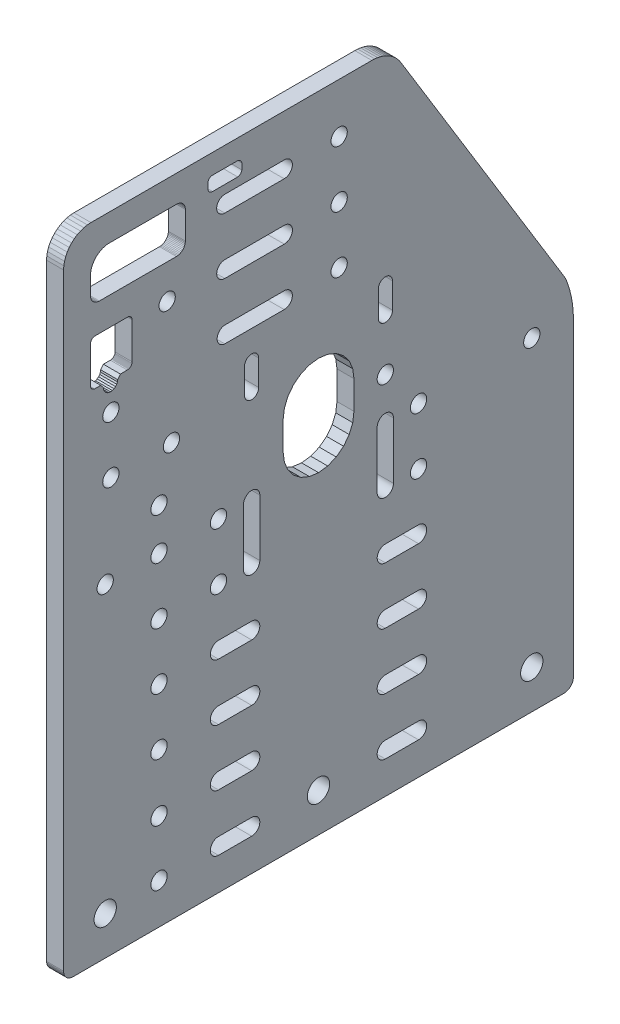
SolidWorks part; units mm, degrees
ref_plane "Front Plane" through (0, 0, 0) normal (0, 0, 1) x (1, 0, 0)
ref_plane "Top Plane" through (0, 0, 0) normal (0, 1, 0) x (1, 0, 0)
ref_plane "Right Plane" through (0, 0, 0) normal (1, 0, 0) x (0, 0, -1)
ref_plane "Plane1" through (0, 0, 0) normal (-1, 0, 0) x (0, -1, 0)
sketch "Sketch1" plane through (0, 0, 0) normal (-1, 0, 0) x (0, -1, 0)
  line L0 (-590.2121, -1614.2437) -> (-495.2304, -1672.3356)
  line L1 (-495.2304, -1672.3356) -> (-492.9855, -1673.1988)
  line L2 (-492.9855, -1673.1988) -> (-490.6881, -1673.9103)
  line L3 (-490.6881, -1673.9103) -> (-488.3483, -1674.4671)
  line L4 (-488.3483, -1674.4671) -> (-485.9766, -1674.8665)
  line L5 (-485.9766, -1674.8665) -> (-483.5835, -1675.1069)
  line L6 (-483.5835, -1675.1069) -> (-481.1798, -1675.1871)
  line L7 (-481.1798, -1675.1871) -> (-371.8266, -1675.1871)
  line L8 (-371.8266, -1675.1871) -> (-371.3877, -1675.1584)
  line L9 (-371.3877, -1675.1584) -> (-370.9562, -1675.0725)
  line L10 (-370.9562, -1675.0725) -> (-370.5397, -1674.9312)
  line L11 (-370.5397, -1674.9312) -> (-370.1452, -1674.7366)
  line L12 (-370.1452, -1674.7366) -> (-369.7795, -1674.4922)
  line L13 (-369.7795, -1674.4922) -> (-369.4487, -1674.2022)
  line L14 (-369.4487, -1674.2022) -> (-369.1587, -1673.8715)
  line L15 (-369.1587, -1673.8715) -> (-368.9143, -1673.5057)
  line L16 (-368.9143, -1673.5057) -> (-368.7198, -1673.1112)
  line L17 (-368.7198, -1673.1112) -> (-368.5784, -1672.6947)
  line L18 (-368.5784, -1672.6947) -> (-368.4926, -1672.2633)
  line L19 (-368.4926, -1672.2633) -> (-368.4638, -1671.8243)
  line L20 (-368.4638, -1671.8243) -> (-368.4638, -1498.5099)
  line L21 (-368.4638, -1498.5099) -> (-368.4926, -1498.071)
  line L22 (-368.4926, -1498.071) -> (-368.5784, -1497.6396)
  line L23 (-368.5784, -1497.6396) -> (-368.7198, -1497.223)
  line L24 (-368.7198, -1497.223) -> (-368.9143, -1496.8285)
  line L25 (-368.9143, -1496.8285) -> (-369.1587, -1496.4628)
  line L26 (-369.1587, -1496.4628) -> (-369.4487, -1496.1321)
  line L27 (-369.4487, -1496.1321) -> (-369.7795, -1495.842)
  line L28 (-369.7795, -1495.842) -> (-370.1452, -1495.5977)
  line L29 (-370.1452, -1495.5977) -> (-370.5397, -1495.4031)
  line L30 (-370.5397, -1495.4031) -> (-370.9562, -1495.2617)
  line L31 (-370.9562, -1495.2617) -> (-371.3877, -1495.1759)
  line L32 (-371.3877, -1495.1759) -> (-371.8266, -1495.1471)
  line L33 (-371.8266, -1495.1471) -> (-586.2881, -1495.1456)
  line L34 (-586.2881, -1495.1456) -> (-587.5497, -1495.2283)
  line L35 (-587.5497, -1495.2283) -> (-588.7897, -1495.475)
  line L36 (-588.7897, -1495.475) -> (-589.987, -1495.8813)
  line L37 (-589.987, -1495.8813) -> (-591.1209, -1496.4405)
  line L38 (-591.1209, -1496.4405) -> (-592.1721, -1497.1429)
  line L39 (-592.1721, -1497.1429) -> (-593.1227, -1497.9766)
  line L40 (-593.1227, -1497.9766) -> (-593.9563, -1498.9271)
  line L41 (-593.9563, -1498.9271) -> (-594.6588, -1499.9784)
  line L42 (-594.6588, -1499.9784) -> (-595.218, -1501.1123)
  line L43 (-595.218, -1501.1123) -> (-595.6244, -1502.3095)
  line L44 (-595.6244, -1502.3095) -> (-595.871, -1503.5495)
  line L45 (-595.871, -1503.5495) -> (-595.9537, -1504.8111)
  line L46 (-595.9537, -1504.8111) -> (-595.9537, -1603.9943)
  line L47 (-595.9537, -1603.9943) -> (-595.9102, -1605.016)
  line L48 (-595.9102, -1605.016) -> (-595.78, -1606.0302)
  line L49 (-595.78, -1606.0302) -> (-595.5641, -1607.0297)
  line L50 (-595.5641, -1607.0297) -> (-595.264, -1608.0073)
  line L51 (-595.264, -1608.0073) -> (-594.8819, -1608.9558)
  line L52 (-594.8819, -1608.9558) -> (-594.4205, -1609.8683)
  line L53 (-594.4205, -1609.8683) -> (-593.8833, -1610.7384)
  line L54 (-593.8833, -1610.7384) -> (-593.274, -1611.5596)
  line L55 (-593.274, -1611.5596) -> (-592.5971, -1612.3261)
  line L56 (-592.5971, -1612.3261) -> (-591.8575, -1613.0323)
  line L57 (-591.8575, -1613.0323) -> (-591.0606, -1613.673)
  line L58 (-591.0606, -1613.673) -> (-590.2121, -1614.2437)
  line L59 (-575.2278, -1552.0779) -> (-575.2278, -1573.0506)
  line L60 (-580.9777, -1573.098) -> (-580.9777, -1552.0841)
  line L61 (-535.2278, -1552.0792) -> (-535.2278, -1573.052)
  line L62 (-540.9777, -1573.0993) -> (-540.9777, -1552.0854)
  line L63 (-555.2276, -1552.095) -> (-555.2276, -1573.0814)
  line L64 (-560.9776, -1573.1131) -> (-560.9776, -1552.0992)
  line L65 (-524.9137, -1559.0552) -> (-515.9137, -1559.0552)
  line L66 (-515.9137, -1564.0552) -> (-524.9137, -1564.0552)
  line L67 (-524.9137, -1606.2991) -> (-515.9137, -1606.2991)
  line L68 (-515.9137, -1611.2991) -> (-524.9137, -1611.2991)
  line L69 (-477.6698, -1606.2991) -> (-468.6699, -1606.2991)
  line L70 (-468.6699, -1611.2991) -> (-477.6698, -1611.2991)
  line L71 (-477.6698, -1559.0528) -> (-468.6699, -1559.0552)
  line L72 (-468.6712, -1564.0552) -> (-477.6698, -1564.0528)
  line L73 (-586.0336, -1536.5791) -> (-586.215, -1536.2112)
  line L74 (-586.215, -1536.2112) -> (-586.3468, -1535.8228)
  line L75 (-586.3468, -1535.8228) -> (-586.4269, -1535.4204)
  line L76 (-586.4269, -1535.4204) -> (-586.4537, -1535.0111)
  line L77 (-586.4537, -1535.0111) -> (-586.4537, -1511.2962)
  line L78 (-586.4537, -1511.2962) -> (-586.3968, -1510.4284)
  line L79 (-586.3968, -1510.4284) -> (-586.2271, -1509.5753)
  line L80 (-586.2271, -1509.5753) -> (-585.9476, -1508.7517)
  line L81 (-585.9476, -1508.7517) -> (-585.5629, -1507.9717)
  line L82 (-585.5629, -1507.9717) -> (-585.0797, -1507.2485)
  line L83 (-585.0797, -1507.2485) -> (-584.5062, -1506.5946)
  line L84 (-584.5062, -1506.5946) -> (-583.8523, -1506.0211)
  line L85 (-583.8523, -1506.0211) -> (-583.1291, -1505.5379)
  line L86 (-583.1291, -1505.5379) -> (-582.3491, -1505.1533)
  line L87 (-582.3491, -1505.1533) -> (-581.5255, -1504.8737)
  line L88 (-581.5255, -1504.8737) -> (-580.6725, -1504.704)
  line L89 (-580.6725, -1504.704) -> (-579.8046, -1504.6471)
  line L90 (-579.8046, -1504.6471) -> (-573.6169, -1504.6471)
  line L91 (-573.6169, -1504.6471) -> (-573.2076, -1504.6739)
  line L92 (-573.2076, -1504.6739) -> (-572.8052, -1504.754)
  line L93 (-572.8052, -1504.754) -> (-572.4168, -1504.8858)
  line L94 (-572.4168, -1504.8858) -> (-572.0489, -1505.0673)
  line L95 (-572.0489, -1505.0673) -> (-571.7078, -1505.2952)
  line L96 (-571.7078, -1505.2952) -> (-571.3994, -1505.5656)
  line L97 (-571.3994, -1505.5656) -> (-571.1289, -1505.8741)
  line L98 (-571.1289, -1505.8741) -> (-570.901, -1506.2151)
  line L99 (-570.901, -1506.2151) -> (-570.7196, -1506.583)
  line L100 (-570.7196, -1506.583) -> (-570.5877, -1506.9715)
  line L101 (-570.5877, -1506.9715) -> (-570.5077, -1507.3738)
  line L102 (-570.5077, -1507.3738) -> (-570.4809, -1507.7831)
  line L103 (-570.4809, -1507.7831) -> (-570.4809, -1535.0111)
  line L104 (-570.4809, -1535.0111) -> (-570.5077, -1535.4204)
  line L105 (-570.5077, -1535.4204) -> (-570.5877, -1535.8228)
  line L106 (-570.5877, -1535.8228) -> (-570.7196, -1536.2112)
  line L107 (-570.7196, -1536.2112) -> (-570.901, -1536.5791)
  line L108 (-570.901, -1536.5791) -> (-571.1289, -1536.9202)
  line L109 (-571.1289, -1536.9202) -> (-571.3994, -1537.2286)
  line L110 (-571.3994, -1537.2286) -> (-571.7078, -1537.4991)
  line L111 (-571.7078, -1537.4991) -> (-572.0489, -1537.727)
  line L112 (-572.0489, -1537.727) -> (-572.4168, -1537.9084)
  line L113 (-572.4168, -1537.9084) -> (-572.8052, -1538.0403)
  line L114 (-572.8052, -1538.0403) -> (-573.2076, -1538.1203)
  line L115 (-573.2076, -1538.1203) -> (-573.6169, -1538.1471)
  line L116 (-573.6169, -1538.1471) -> (-583.3177, -1538.1471)
  line L117 (-583.3177, -1538.1471) -> (-583.727, -1538.1203)
  line L118 (-583.727, -1538.1203) -> (-584.1293, -1538.0403)
  line L119 (-584.1293, -1538.0403) -> (-584.5178, -1537.9084)
  line L120 (-584.5178, -1537.9084) -> (-584.8857, -1537.727)
  line L121 (-584.8857, -1537.727) -> (-585.2268, -1537.4991)
  line L122 (-585.2268, -1537.4991) -> (-585.5352, -1537.2286)
  line L123 (-585.5352, -1537.2286) -> (-585.8057, -1536.9202)
  line L124 (-585.8057, -1536.9202) -> (-586.0336, -1536.5791)
  line L125 (-560.5397, -1505.8783) -> (-560.4696, -1505.6715)
  line L126 (-560.4696, -1505.6715) -> (-560.373, -1505.4757)
  line L127 (-560.373, -1505.4757) -> (-560.2517, -1505.2942)
  line L128 (-560.2517, -1505.2942) -> (-560.1078, -1505.1301)
  line L129 (-560.1078, -1505.1301) -> (-559.9436, -1504.9862)
  line L130 (-559.9436, -1504.9862) -> (-559.7621, -1504.8649)
  line L131 (-559.7621, -1504.8649) -> (-559.5663, -1504.7683)
  line L132 (-559.5663, -1504.7683) -> (-559.3596, -1504.6981)
  line L133 (-559.3596, -1504.6981) -> (-559.1312, -1504.6471)
  line L134 (-559.1312, -1504.6471) -> (-558.9276, -1504.6413)
  line L135 (-558.9276, -1504.6413) -> (-548.4809, -1504.6452)
  line L136 (-548.4809, -1504.6452) -> (-545.8818, -1504.6452)
  line L137 (-545.8818, -1504.6452) -> (-545.6677, -1504.6877)
  line L138 (-545.6677, -1504.6877) -> (-545.461, -1504.7579)
  line L139 (-545.461, -1504.7579) -> (-545.2652, -1504.8545)
  line L140 (-545.2652, -1504.8545) -> (-545.0837, -1504.9758)
  line L141 (-545.0837, -1504.9758) -> (-544.9196, -1505.1197)
  line L142 (-544.9196, -1505.1197) -> (-544.7756, -1505.2838)
  line L143 (-544.7756, -1505.2838) -> (-544.6543, -1505.4654)
  line L144 (-544.6543, -1505.4654) -> (-544.5578, -1505.6612)
  line L145 (-544.5578, -1505.6612) -> (-544.4876, -1505.8679)
  line L146 (-544.4876, -1505.8679) -> (-544.445, -1506.082)
  line L147 (-544.445, -1506.082) -> (-544.4414, -1508.2677)
  line L148 (-544.4414, -1508.2677) -> (-543.221, -1509.2377)
  line L149 (-543.221, -1509.2377) -> (-542.574, -1509.3226)
  line L150 (-542.574, -1509.3226) -> (-541.9709, -1509.5721)
  line L151 (-541.9709, -1509.5721) -> (-541.453, -1509.9692)
  line L152 (-541.453, -1509.9692) -> (-541.0555, -1510.4868)
  line L153 (-541.0555, -1510.4868) -> (-540.8055, -1511.0897)
  line L154 (-540.8055, -1511.0897) -> (-540.72, -1511.7367)
  line L155 (-540.72, -1511.7367) -> (-540.805, -1512.3838)
  line L156 (-540.805, -1512.3838) -> (-541.0545, -1512.9868)
  line L157 (-541.0545, -1512.9868) -> (-541.4516, -1513.5047)
  line L158 (-541.4516, -1513.5047) -> (-541.9692, -1513.9022)
  line L159 (-541.9692, -1513.9022) -> (-542.572, -1514.1522)
  line L160 (-542.572, -1514.1522) -> (-543.219, -1514.2377)
  line L161 (-543.219, -1514.2377) -> (-544.4323, -1515.2077)
  line L162 (-544.4323, -1515.2077) -> (-544.4307, -1517.6776)
  line L163 (-544.4307, -1517.6776) -> (-544.4876, -1518.1096)
  line L164 (-544.4876, -1518.1096) -> (-544.5578, -1518.3163)
  line L165 (-544.5578, -1518.3163) -> (-544.6543, -1518.5121)
  line L166 (-544.6543, -1518.5121) -> (-544.7756, -1518.6936)
  line L167 (-544.7756, -1518.6936) -> (-544.9196, -1518.8578)
  line L168 (-544.9196, -1518.8578) -> (-545.0837, -1519.0017)
  line L169 (-545.0837, -1519.0017) -> (-545.2652, -1519.123)
  line L170 (-545.2652, -1519.123) -> (-545.461, -1519.2196)
  line L171 (-545.461, -1519.2196) -> (-545.6677, -1519.2897)
  line L172 (-545.6677, -1519.2897) -> (-546.0997, -1519.3486)
  line L173 (-546.0997, -1519.3486) -> (-558.9578, -1519.3427)
  line L174 (-558.9578, -1519.3427) -> (-559.1455, -1519.3427)
  line L175 (-559.1455, -1519.3427) -> (-559.3596, -1519.3001)
  line L176 (-559.3596, -1519.3001) -> (-559.5663, -1519.23)
  line L177 (-559.5663, -1519.23) -> (-559.7621, -1519.1334)
  line L178 (-559.7621, -1519.1334) -> (-559.9436, -1519.0121)
  line L179 (-559.9436, -1519.0121) -> (-560.1078, -1518.8682)
  line L180 (-560.1078, -1518.8682) -> (-560.2517, -1518.704)
  line L181 (-560.2517, -1518.704) -> (-560.373, -1518.5225)
  line L182 (-560.373, -1518.5225) -> (-560.4696, -1518.3267)
  line L183 (-560.4696, -1518.3267) -> (-560.5397, -1518.12)
  line L184 (-560.5397, -1518.12) -> (-560.5823, -1517.9059)
  line L185 (-560.5823, -1517.9059) -> (-560.5823, -1517.6796)
  line L186 (-560.5823, -1517.6796) -> (-560.568, -1506.084)
  line L187 (-560.568, -1506.084) -> (-560.5397, -1505.8783)
  line L188 (-512.6093, -1578.9371) -> (-510.6228, -1576.3483)
  line L189 (-510.6228, -1576.3483) -> (-508.034, -1574.3618)
  line L190 (-508.034, -1574.3618) -> (-505.0192, -1573.1131)
  line L191 (-505.0192, -1573.1131) -> (-501.784, -1572.6871)
  line L192 (-501.784, -1572.6871) -> (-491.784, -1572.6871)
  line L193 (-491.784, -1572.6871) -> (-488.5487, -1573.1131)
  line L194 (-488.5487, -1573.1131) -> (-485.534, -1574.3618)
  line L195 (-485.534, -1574.3618) -> (-482.9451, -1576.3483)
  line L196 (-482.9451, -1576.3483) -> (-480.9587, -1578.9371)
  line L197 (-480.9587, -1578.9371) -> (-479.7099, -1581.9519)
  line L198 (-479.7099, -1581.9519) -> (-479.284, -1585.1871)
  line L199 (-479.284, -1585.1871) -> (-479.7099, -1588.4224)
  line L200 (-479.7099, -1588.4224) -> (-480.9587, -1591.4371)
  line L201 (-480.9587, -1591.4371) -> (-482.9451, -1594.026)
  line L202 (-482.9451, -1594.026) -> (-485.534, -1596.0125)
  line L203 (-485.534, -1596.0125) -> (-488.5487, -1597.2612)
  line L204 (-488.5487, -1597.2612) -> (-491.784, -1597.6871)
  line L205 (-491.784, -1597.6871) -> (-501.784, -1597.6871)
  line L206 (-501.784, -1597.6871) -> (-505.0192, -1597.2612)
  line L207 (-505.0192, -1597.2612) -> (-508.034, -1596.0125)
  line L208 (-508.034, -1596.0125) -> (-510.6228, -1594.026)
  line L209 (-510.6228, -1594.026) -> (-512.6093, -1591.4371)
  line L210 (-512.6093, -1591.4371) -> (-513.858, -1588.4224)
  line L211 (-513.858, -1588.4224) -> (-514.284, -1585.1871)
  line L212 (-514.284, -1585.1871) -> (-513.858, -1581.9519)
  line L213 (-513.858, -1581.9519) -> (-512.6093, -1578.9371)
  line L214 (-588.9809, -1556.6482) -> (-588.9809, -1547.5504)
  line L215 (-587.544, -1546.1136) -> (-585.6436, -1546.0993)
  line L216 (-583.9746, -1547.7683) -> (-583.9889, -1556.6482)
  line L217 (-585.4257, -1558.085) -> (-587.544, -1558.085)
  arc A0 (-580.9777, -1552.0841) -> (-575.2278, -1552.0779) centre (-578.1027, -1552.081) cw
  arc A1 (-575.2278, -1573.0506) -> (-580.9777, -1573.098) centre (-578.1027, -1573.0743) cw
  arc A2 (-540.9777, -1552.0854) -> (-535.2278, -1552.0792) centre (-538.1026, -1552.2511) cw
  arc A3 (-535.2278, -1573.052) -> (-540.9777, -1573.0993) centre (-538.1028, -1573.0757) cw
  arc A4 (-560.9776, -1552.0992) -> (-555.2276, -1552.095) centre (-558.1026, -1552.0971) cw
  arc A5 (-555.2276, -1573.0814) -> (-560.9776, -1573.1131) centre (-558.1026, -1573.0972) cw
  arc A6 (-515.9137, -1559.0552) -> (-515.9137, -1564.0552) centre (-515.9137, -1561.5552) cw
  arc A7 (-524.9137, -1564.0552) -> (-524.9137, -1559.0552) centre (-524.9137, -1561.5552) cw
  arc A8 (-515.9137, -1606.2991) -> (-515.9137, -1611.2991) centre (-515.9137, -1608.7991) cw
  arc A9 (-524.9137, -1611.2991) -> (-524.9137, -1606.2991) centre (-524.9137, -1608.7991) cw
  arc A10 (-468.6699, -1606.2991) -> (-468.6699, -1611.2991) centre (-468.6699, -1608.7991) cw
  arc A11 (-477.6698, -1611.2991) -> (-477.6698, -1606.2991) centre (-477.6698, -1608.7991) cw
  arc A12 (-468.6699, -1559.0552) -> (-468.6712, -1564.0552) centre (-468.6705, -1561.5552) cw
  arc A13 (-477.6698, -1564.0528) -> (-477.6698, -1559.0528) centre (-477.6692, -1561.5528) cw
  circle A14 centre (-382.1591, -1509.8471) radius 3.9435
  circle A15 centre (-382.1591, -1585.1671) radius 3.9435
  circle A16 centre (-382.1591, -1660.4871) radius 3.9435
  circle A17 centre (-538.3993, -1592.4578) radius 2.875
  circle A18 centre (-558.4485, -1592.4578) radius 2.875
  circle A19 centre (-578.4485, -1592.4578) radius 2.875
  circle A20 centre (-534.4436, -1511.8471) radius 2.875
  circle A21 centre (-558.4024, -1531.723) radius 2.875
  circle A22 centre (-514.4436, -1511.8471) radius 2.875
  circle A23 centre (-514.4436, -1533.239) radius 2.875
  circle A24 centre (-497.4962, -1528.8471) radius 2.875
  circle A25 centre (-482.7991, -1549.8471) radius 2.875
  circle A26 centre (-482.7991, -1509.8471) radius 2.875
  circle A27 centre (-482.7991, -1620.4871) radius 2.875
  circle A28 centre (-482.7991, -1660.4871) radius 2.875
  circle A29 centre (-402.4962, -1528.8471) radius 2.875
  arc A30 (-588.9809, -1547.5504) -> (-587.544, -1546.1136) centre (-587.3137, -1547.7807) cw
  arc A31 (-585.6436, -1546.0993) -> (-583.9746, -1547.7683) centre (-585.6436, -1547.7683) cw
  arc A32 (-583.9889, -1556.6482) -> (-585.4257, -1558.085) centre (-585.656, -1556.4179) cw
  arc A33 (-587.544, -1558.085) -> (-588.9809, -1556.6482) centre (-587.3262, -1556.4303) cw
  dimension "D1" = 7.887
  dimension "D2" = 5.75
  dimension "D3" = 5.75
  dimension "D4" = 2.5
  dimension "D5" = 5.75
  dimension "D6" = 5.75
  dimension "D7" = 2.875
extrude "Boss-Extrude1" add sketch "Sketch1" against normal blind 6
sketch "Sketch2" plane through (6, 0, 0) normal (1, 0, 0) x (0, 0, -1)
  line L0 (1561.5671, 482.7991) -> (1561.5671, 462.7991) construction
  line L1 (1564.4421, 482.7991) -> (1564.4421, 462.7991)
  line L2 (1558.6921, 482.7991) -> (1558.6921, 462.7991)
  line L3 (1608.7671, 482.7991) -> (1608.7671, 462.7991) construction
  line L4 (1611.6421, 482.7991) -> (1611.6421, 462.7991)
  line L5 (1605.8921, 482.7991) -> (1605.8921, 462.7991)
  line L6 (1620.4871, 442.7991) -> (1608.7671, 442.7991) construction
  line L7 (1620.4871, 439.9241) -> (1608.7671, 439.9241)
  line L8 (1620.4871, 445.6741) -> (1608.7671, 445.6741)
  line L9 (1620.4871, 422.7991) -> (1608.7671, 422.7991) construction
  line L10 (1620.4871, 419.9241) -> (1608.7671, 419.9241)
  line L11 (1620.4871, 425.6741) -> (1608.7671, 425.6741)
  line L12 (1620.4871, 402.7991) -> (1608.7671, 402.7991) construction
  line L13 (1620.4871, 399.9241) -> (1608.7671, 399.9241)
  line L14 (1620.4871, 405.6741) -> (1608.7671, 405.6741)
  line L15 (1620.4871, 382.7991) -> (1608.7671, 382.7991) construction
  line L16 (1620.4871, 379.9241) -> (1608.7671, 379.9241)
  line L17 (1620.4871, 385.6741) -> (1608.7671, 385.6741)
  line L18 (1561.5671, 442.7991) -> (1549.8471, 442.7991) construction
  line L19 (1561.5671, 439.9241) -> (1549.8471, 439.9241)
  line L20 (1561.5671, 445.6741) -> (1549.8471, 445.6741)
  line L21 (1561.5671, 422.7991) -> (1549.8471, 422.7991) construction
  line L22 (1561.5671, 419.9241) -> (1549.8471, 419.9241)
  line L23 (1561.5671, 425.6741) -> (1549.8471, 425.6741)
  line L24 (1561.5671, 402.7991) -> (1549.8471, 402.7991) construction
  line L25 (1561.5671, 399.9241) -> (1549.8471, 399.9241)
  line L26 (1561.5671, 405.6741) -> (1549.8471, 405.6741)
  line L27 (1561.5671, 382.7991) -> (1549.8471, 382.7991) construction
  line L28 (1561.5671, 379.9241) -> (1549.8471, 379.9241)
  line L29 (1561.5671, 385.6741) -> (1549.8471, 385.6741)
  circle A0 centre (1608.7671, 442.7991) radius 2.875 construction
  circle A26 centre (1620.4871, 402.7991) radius 2.875 construction
  circle A27 centre (1620.4871, 482.7991) radius 2.875 construction
  circle A28 centre (1549.8471, 482.7991) radius 2.875 construction
  circle A29 centre (1620.4871, 482.7991) radius 2.875
  circle A30 centre (1549.8471, 482.7991) radius 2.875
  arc A32 (1564.4421, 482.7991) -> (1558.6921, 482.7991) centre (1561.5671, 482.7991) ccw
  circle A35 centre (1549.8471, 462.7991) radius 2.875
  circle A36 centre (1620.4871, 462.7991) radius 2.875
  circle A39 centre (1549.8471, 442.7991) radius 2.875 construction
  circle A40 centre (1620.4871, 442.7991) radius 2.875 construction
  circle A43 centre (1549.8471, 422.7991) radius 2.875 construction
  circle A44 centre (1620.4871, 422.7991) radius 2.875 construction
  circle A47 centre (1549.8471, 402.7991) radius 2.875 construction
  circle A49 centre (1549.8471, 382.7991) radius 2.875 construction
  circle A51 centre (1620.4871, 382.7991) radius 2.875 construction
  circle A52 centre (1608.7671, 422.7991) radius 2.875 construction
  circle A53 centre (1608.7671, 382.7991) radius 2.875 construction
  arc A54 (1558.6921, 462.7991) -> (1564.4421, 462.7991) centre (1561.5671, 462.7991) ccw
  circle A55 centre (1561.5671, 442.7991) radius 2.875 construction
  circle A56 centre (1561.5671, 422.7991) radius 2.875 construction
  circle A57 centre (1561.5671, 402.7991) radius 2.875 construction
  circle A58 centre (1561.5671, 382.7991) radius 2.875 construction
  circle A61 centre (1608.7671, 402.7991) radius 2.875 construction
  arc A62 (1611.6421, 482.7991) -> (1605.8921, 482.7991) centre (1608.7671, 482.7991) ccw
  arc A63 (1605.8921, 462.7991) -> (1611.6421, 462.7991) centre (1608.7671, 462.7991) ccw
  arc A64 (1611.6421, 482.7991) -> (1605.8921, 482.7991) centre (1608.7671, 482.7991) ccw
  arc A65 (1605.8921, 462.7991) -> (1611.6421, 462.7991) centre (1608.7671, 462.7991) ccw
  circle A66 centre (1528.8471, 497.4962) radius 2.875 construction
  circle A67 centre (1528.8471, 497.4962) radius 2.875
  circle A68 centre (1608.7671, 497.4962) radius 2.875
  circle A69 centre (1528.8471, 482.7962) radius 2.875
  circle A70 centre (1528.8471, 462.7861) radius 2.875
  circle A71 centre (1528.8471, 442.7761) radius 2.875
  circle A72 centre (1528.8471, 422.766) radius 2.875
  circle A74 centre (1528.8471, 382.7459) radius 2.875
  circle A75 centre (1528.8471, 402.756) radius 2.875 [skipped]
  arc A76 (1620.4871, 439.9241) -> (1620.4871, 445.6741) centre (1620.4871, 442.7991) ccw
  arc A77 (1608.7671, 445.6741) -> (1608.7671, 439.9241) centre (1608.7671, 442.7991) ccw
  arc A78 (1620.4871, 419.9241) -> (1620.4871, 425.6741) centre (1620.4871, 422.7991) ccw
  arc A79 (1608.7671, 425.6741) -> (1608.7671, 419.9241) centre (1608.7671, 422.7991) ccw
  arc A80 (1620.4871, 399.9241) -> (1620.4871, 405.6741) centre (1620.4871, 402.7991) ccw
  arc A81 (1608.7671, 405.6741) -> (1608.7671, 399.9241) centre (1608.7671, 402.7991) ccw
  arc A82 (1620.4871, 379.9241) -> (1620.4871, 385.6741) centre (1620.4871, 382.7991) ccw
  arc A83 (1608.7671, 385.6741) -> (1608.7671, 379.9241) centre (1608.7671, 382.7991) ccw
  arc A84 (1561.5671, 439.9241) -> (1561.5671, 445.6741) centre (1561.5671, 442.7991) ccw
  arc A85 (1549.8471, 445.6741) -> (1549.8471, 439.9241) centre (1549.8471, 442.7991) ccw
  arc A86 (1561.5671, 419.9241) -> (1561.5671, 425.6741) centre (1561.5671, 422.7991) ccw
  arc A87 (1549.8471, 425.6741) -> (1549.8471, 419.9241) centre (1549.8471, 422.7991) ccw
  arc A88 (1561.5671, 399.9241) -> (1561.5671, 405.6741) centre (1561.5671, 402.7991) ccw
  arc A89 (1549.8471, 405.6741) -> (1549.8471, 399.9241) centre (1549.8471, 402.7991) ccw
  arc A90 (1561.5671, 379.9241) -> (1561.5671, 385.6741) centre (1561.5671, 382.7991) ccw
  arc A91 (1549.8471, 385.6741) -> (1549.8471, 379.9241) centre (1549.8471, 382.7991) ccw
  point P19 (1608.7671, 472.7991)
  point P48 (1614.6271, 442.7991)
  point P54 (1561.5671, 472.7991)
  point P80 (1614.6271, 422.7991)
  point P85 (1614.6271, 402.7991)
  point P92 (1614.6271, 382.7991)
  point P97 (1555.7071, 442.7991)
  point P102 (1555.7071, 422.7991)
  point P107 (1555.7071, 402.7991)
  point P112 (1555.7071, 382.7991)
  dimension "D4" = 79.92
  dimension "D10" = 14.7
  dimension "D13" = 5.75
  dimension "D14" = 11.72
  dimension "D16" = 5.75
  dimension "D17" = 11.72
  dimension "D18" = 5.75
  dimension "D19" = 11.72
  dimension "D20" = 5.75
  dimension "D21" = 11.72
  dimension "D22" = 5.75
  dimension "D23" = 11.72
  dimension "D24" = 5.75
  dimension "D25" = 11.72
  dimension "D26" = 5.75
  dimension "D27" = 11.72
  dimension "D28" = 5.75
  dimension "D29" = 11.72
  dimension "D31" = 5.75
  dimension "D5" = 4
  dimension "D6" = 3
  dimension "D8" = 2
  dimension "D12" = 2
  dimension "D15" = 2
  dimension "D2" = 6
  dimension "D3" = 2
  dimension "D30" = 2
  dimension "D7" = 2
  dimension "D9" = 2
  dimension "D11" = 6
extrude "Cut-Extrude3" cut sketch "Sketch2" against normal through all contours L5 A63 L4 A62 | A39 | A30 | A35 | A43 | A47 | A49 | A58 | A57 | A56 | A55 | L1 A54 L2 A32 | A36 | A61 | A53 | A51 | A26 | A44 | A52 | A0 | A40 | A29 | A68 | A74 | A70 | A71 | A69 | A72 | L8 A77 L7 A76 | L11 A79 L10 A78 | L14 A81 L13 A80 | L17 A82 L16 A83 | L29 A91 L28 A90 | L26 A89 L25 A88 | L23 A87 L22 A86 | L20 A85 L19 A84
equation "\"holeMOD\"= 0.75mm"
equation "\"D1@Sketch1\" = 7.137mm + \"holeMOD\""
equation "\"D2@Sketch1\" = 5.00mm + \"holeMOD\""
equation "\"D3@Sketch1\" = 5.00mm + \"holeMOD\""
equation "\"D4@Sketch1\"=2.50mm"
equation "\"D5@Sketch1\" = 5.00mm + \"holeMOD\""
equation "\"D6@Sketch1\" = 5.00mm + \"holeMOD\""
equation "\"D7@Sketch1\" = 2.50004757mm + \"holeMOD\" / 2"
equation "\"D20@Sketch2\" = 5.00mm + \"holeMOD\""
equation "\"D18@Sketch2\" = 5.00mm + \"holeMOD\""
equation "\"D16@Sketch2\" = 5.00mm + \"holeMOD\""
equation "\"D13@Sketch2\" = 5.00mm + \"holeMOD\""
equation "\"D28@Sketch2\" = 5.00mm + \"holeMOD\""
equation "\"D26@Sketch2\" = 5.00mm + \"holeMOD\""
equation "\"D24@Sketch2\" = 5.00mm + \"holeMOD\""
equation "\"D22@Sketch2\" = 5.00mm + \"holeMOD\""
equation "\"D31@Sketch2\" = 5.00mm + \"holeMOD\""
